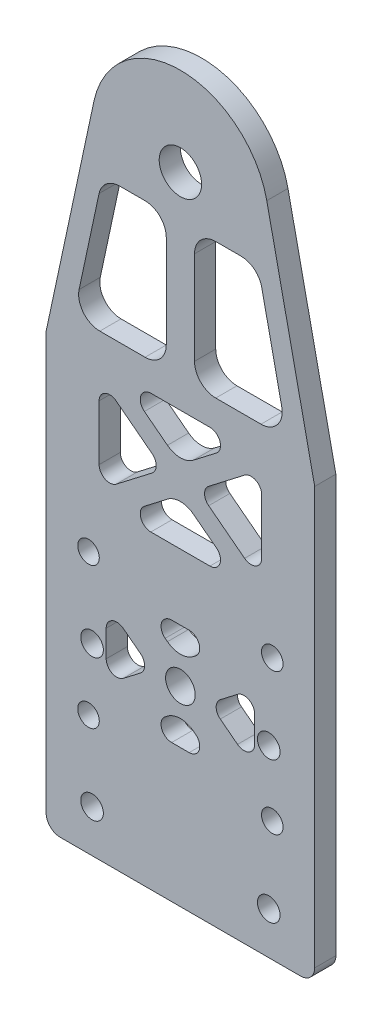
SolidWorks part; units mm, degrees
material "Thornel Mat VMA"
ref_plane "前视基准面" through (0, 0, 0) normal (0, 0, 1) x (1, 0, 0)
ref_plane "上视基准面" through (0, 0, 0) normal (0, 1, 0) x (1, 0, 0)
ref_plane "右视基准面" through (0, 0, 0) normal (1, 0, 0) x (0, 0, -1)
sketch "草图1" plane through (0, 0, 0) normal (0, 0, 1) x (1, 0, 0)
  line L0 (0, 0) -> (0, -40) construction
  line L1 (-19, -40) -> (19, -40)
  line L2 (19, -40) -> (19, -29)
  line L3 (19, -29) -> (12.2224, 2.6198)
  line L4 (-19, -29) -> (-12.2224, 2.6198)
  line L5 (-19, -40) -> (-19, -29)
  circle A0 centre (0, 0) radius 3
  arc A1 (12.2224, 2.6198) -> (-12.2224, 2.6198) centre (0, 0) ccw
  point P8 (0, -40)
  dimension "D1" = 6
  dimension "D2" = 25
  dimension "D3" = 40
  dimension "D4" = 38
  dimension "D5" = 11
extrude "凸台-拉伸1" add sketch "草图1" along normal blind 3
sketch "草图2" plane through (0, 0, 3) normal (0, 0, 1) x (1, 0, 0)
  line L0 (-12.5, -84) -> (12.5, -84) construction
  line L1 (-19, -40) -> (19, -40)
  line L2 (-19, -40) -> (-19, -90)
  line L3 (-19, -90) -> (19, -90)
  line L4 (19, -40) -> (19, -90)
  line L5 (0, 0) -> (0, -84) construction
  circle A0 centre (-12.5, -84) radius 1.6
  circle A1 centre (12.5, -84) radius 1.6
  dimension "D3" = 3.2
  dimension "D1" = 90
  dimension "D2" = 6
  dimension "D4" = 25
extrude "凸台-拉伸2" add sketch "草图2" against normal blind 3
sketch "草图13" plane through (0, 0, 3) normal (0, 0, 1) x (1, 0, 0)
  line L0 (0, 0) -> (0, -90) construction
  line L1 (-13, -53) -> (13, -53) construction
  line L2 (-13, -53) -> (-13, -73) construction
  line L3 (-13, -73) -> (13, -73) construction
  line L4 (13, -53) -> (13, -73) construction
  line L5 (-13, -53) -> (13, -73) construction
  line L6 (-13, -73) -> (13, -53) construction
  line L7 (-19, -90) -> (19, -90) construction
  circle A0 centre (12.5, -84) radius 1.6 construction
  circle A1 centre (-13, -53) radius 1.525
  circle A2 centre (-13, -73) radius 1.525
  circle A3 centre (13, -53) radius 1.525
  circle A4 centre (13, -73) radius 1.525
  point P0 (0, -63)
  dimension "D4" = 3.05
  dimension "D1" = 26
  dimension "D2" = 20
  dimension "D3" = 11
extrude "切除-拉伸8" cut sketch "草图13" against normal blind 10
sketch "草图14" plane through (0, 0, 3) normal (0, 0, 1) x (1, 0, 0)
  line L0 (-13, -73) -> (13, -53)
  line L1 (-13, -53) -> (13, -73)
  line L2 (-13, -53) -> (13, -53)
  line L3 (13, -53) -> (13, -73)
  line L4 (13, -73) -> (-13, -73)
  line L5 (-13, -73) -> (-13, -53)
  line L6 (-10.5, -73) -> (-10.5, -53)
  line L7 (-13, -55.5) -> (13, -55.5)
  line L8 (10.5, -53) -> (10.5, -73)
  line L9 (13, -70.5) -> (-13, -70.5)
  line L10 (-14.5243, -54.9816) -> (11.4757, -74.9816)
  line L11 (-11.4757, -74.9816) -> (14.5243, -54.9816)
  line L12 (-13.0015, -47.6761) -> (12.9985, -27.6761)
  line L13 (-13.0015, -27.6761) -> (12.9985, -47.6761)
  line L14 (-13.0015, -27.6761) -> (12.9985, -27.6761)
  line L15 (12.9985, -27.6761) -> (12.9985, -47.6761)
  line L16 (-11.4757, -51.0184) -> (14.5243, -71.0184)
  line L17 (-14.5243, -71.0184) -> (11.4757, -51.0184)
  line L18 (12.9985, -47.6761) -> (-13.0015, -47.6761)
  line L19 (-13.0015, -47.6761) -> (-13.0015, -27.6761)
  line L20 (-11.5015, -47.6761) -> (-11.5015, -27.6761)
  line L21 (-13.0015, -29.1761) -> (12.9985, -29.1761)
  line L22 (11.4985, -27.6761) -> (11.4985, -47.6761)
  line L23 (12.9985, -46.1761) -> (-13.0015, -46.1761)
  line L24 (-13.9161, -28.865) -> (12.0839, -48.865)
  line L25 (-12.087, -48.865) -> (13.913, -28.865)
  line L26 (-12.087, -26.4871) -> (13.913, -46.4871)
  line L27 (-13.9161, -46.4871) -> (12.0839, -26.4871)
  line L28 (0, 0) -> (0, -63) construction
  dimension "D1" = 2.5
  dimension "D2" = 2.5
extrude "切除-拉伸9" cut sketch "草图14" against normal blind 10 contours L28 L7 L16 | L7 L28 L17 | L6 L17 L10 | L11 L9 L10 | L11 L16 L8 | L24 L28 L23 | L28 L24 L25 L23 | L20 L27 L24 | L28 L21 L26 L27 | L21 L28 L27 | L25 L26 L22
sketch "草图16" plane through (0, 0, 3) normal (0, 0, 1) x (1, 0, 0)
  line L0 (0, -6) -> (0, -25.1761)
  line L3 (-2, -6) -> (-2, -25.1761)
  line L5 (-2, -6) -> (-11.0019, -6)
  line L6 (-11.0019, -6) -> (-15.1122, -25.1761)
  line L7 (-15.1122, -25.1761) -> (-2, -25.1761)
  line L11 (-12.2224, 2.6198) -> (-19, -29) construction
  line L13 (-8.5913, -29.1761) -> (8.5883, -29.1761) construction
  line L14 (11.0019, -6) -> (15.1122, -25.1761)
  line L15 (2, -6) -> (11.0019, -6)
  line L16 (2, -6) -> (2, -25.1761)
  line L17 (15.1122, -25.1761) -> (2, -25.1761)
  dimension "D3" = 3
  dimension "D4" = 6
  dimension "D2" = 4
  dimension "D1" = 2
extrude "切除-拉伸10" cut sketch "草图16" against normal blind 10 contours L6 L7 L3 L5 | L17 L14 L15 L16
fillet "圆角7" radius 3 12 edges at (0, -66.1541, 1.5) (0, -59.8459, 1.5) (-0.0015, -39.5685, 1.5) (-0.0015, -35.7836, 1.5) (15.1122, -25.1761, 1.5) (2, -25.1761, 1.5) (-2, -25.1761, 1.5) (-15.1122, -25.1761, 1.5) (2, -6, 1.5) (11.0019, -6, 1.5) (-2, -6, 1.5) (-11.0019, -6, 1.5)
fillet "圆角8" radius 1.5 20 edges at (11.4985, -44.6298, 1.5) (-2.4617, -37.6761, 1.5) (2.4587, -37.6761, 1.5) (11.4985, -30.7224, 1.5) (8.5883, -29.1761, 1.5) (-8.5913, -29.1761, 1.5) (-11.5015, -30.7224, 1.5) (-11.5015, -44.6298, 1.5) (8.5883, -46.1761, 1.5) (-8.5913, -46.1761, 1.5) (10.5, -67.9228, 1.5) (5.6497, -70.5, 1.5) (5.6497, -55.5, 1.5) (-4.1003, -63, 1.5) (4.1003, -63, 1.5) (-5.6497, -55.5, 1.5) (-5.6497, -70.5, 1.5) (-10.5, -67.9228, 1.5) (-10.5, -58.0772, 1.5) (10.5, -58.0772, 1.5)
sketch "草图18" plane through (0, 0, 0) normal (0, 0, -1) x (-1, 0, 0)
  circle A0 centre (0, -63) radius 2.1
  dimension "D1" = 4.2
extrude "切除-拉伸11" cut sketch "草图18" against normal blind 3
sketch "草图3" plane through (0, 0, 0) normal (0, 0, -1) x (-1, 0, 0)
  line L1 (19, -29) -> (19, -90) construction
  circle A0 centre (-6, -44) radius 1.6
  circle A1 centre (14, -44) radius 1.6
  dimension "D3" = 3.2
  dimension "D1" = 20
  dimension "D2" = 5
  dimension "D4" = 15
fillet "圆角2" radius 2 2 edges at (19, -90, 1.5) (-19, -90, 1.5)
sketch "草图12" plane through (0, 0, 3) normal (0, 0, 1) x (1, 0, 0)
  line L1 (-12.5, -84) -> (12.5, -84) construction
  line L2 (-12.5, -84) -> (-12.5, -64) construction
  line L3 (-12.5, -64) -> (12.5, -64) construction
  line L4 (12.5, -84) -> (12.5, -64) construction
  circle A0 centre (12.5, -84) radius 1.6 construction
  circle A1 centre (-12.5, -64) radius 1.6
  circle A2 centre (12.5, -64) radius 1.6
  circle A3 centre (-12.5, -84) radius 1.6 construction
  dimension "D1" = 20
extrude "切除-拉伸7" cut sketch "草图12" against normal blind 10
